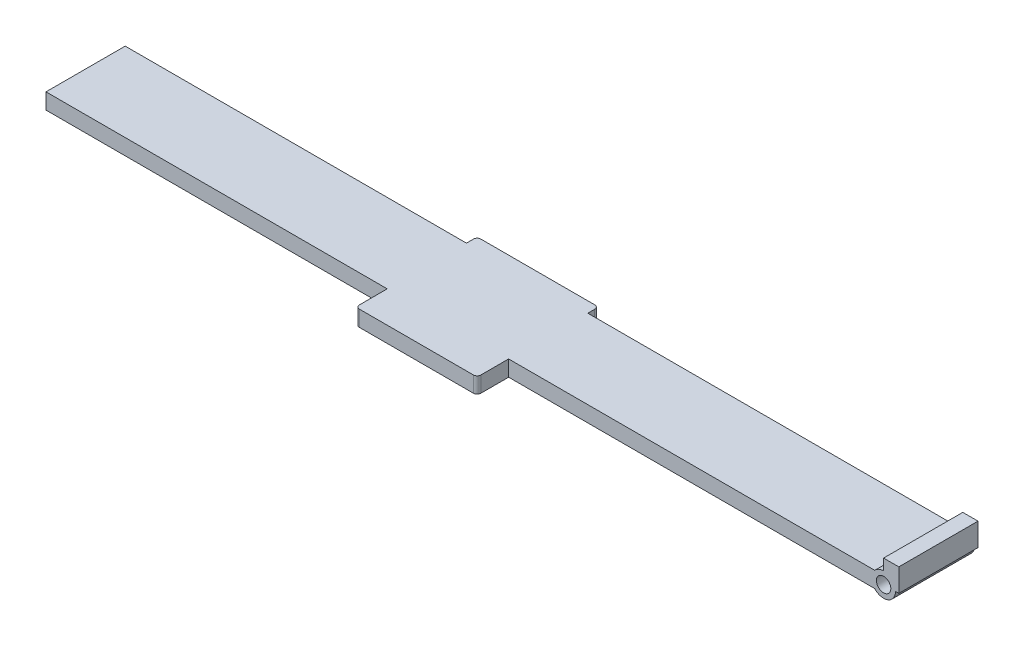
SolidWorks part; units mm, degrees
ref_plane "Front Plane" through (0, 0, 0) normal (0, 0, 1) x (1, 0, 0)
ref_plane "Top Plane" through (0, 0, 0) normal (0, 1, 0) x (1, 0, 0)
ref_plane "Right Plane" through (0, 0, 0) normal (1, 0, 0) x (0, 0, -1)
sketch "Sketch1" plane through (0, 0, 0) normal (0, 1, 0) x (1, 0, 0)
  line L1 (-264.4, -25) -> (264.4, -25)
  line L2 (-264.4, -25) -> (-264.4, 25)
  line L3 (-264.4, 25) -> (264.4, 25)
  line L4 (264.4, -25) -> (264.4, 25)
  line L5 (-264.4, -25) -> (264.4, 25) construction
  line L6 (-264.4, 25) -> (264.4, -25) construction
  point P0 (0, 0)
  dimension "D1" = 528.8
  dimension "D2" = 50
extrude "Extrude2" add sketch "Sketch1" along normal blind 10
sketch "Sketch2" plane through (0, 0, 25) normal (0, 0, 1) x (1, 0, 0)
  line L0 (264.4, 10) -> (264.4, 0) construction
  circle A0 centre (264.4, 5) radius 7.5
  dimension "D1" = 15
extrude "Extrude3" add sketch "Sketch2" against normal blind 50
sketch "Sketch3" plane through (0, 0, 25) normal (0, 0, 1) x (1, 0, 0)
  line L1 (264.4, 5) -> (273.9998, 5)
  line L2 (264.4, 5) -> (264.4, 19.4848)
  line L3 (264.4, 19.4848) -> (273.9998, 19.4848)
  line L4 (273.9998, 5) -> (273.9998, 19.4848)
extrude "Extrude4" add sketch "Sketch3" against normal blind 50
sketch "Sketch5" plane through (0, 0, 25) normal (0, 0, 1) x (1, 0, 0)
  circle A0 centre (264.4, 5) radius 4.5502
extrude "Extrude5" cut sketch "Sketch5" against normal blind 50
sketch "Sketch6" plane through (0, 0, 0) normal (0, 1, 0) x (1, 0, 0)
  line L4 (-48.9687, 29.3464) -> (-48.9687, -42.4541)
  line L5 (-46.548, -44.8747) -> (25.2525, -44.8747)
  line L6 (27.6731, -42.4541) -> (27.6731, 29.3464)
  line L7 (25.2525, 31.7671) -> (-46.548, 31.7671)
  line L8 (-48.9687, 29.3464) -> (-48.9687, -42.4541)
  line L9 (-46.548, -44.8747) -> (25.2525, -44.8747)
  line L10 (27.6731, -42.4541) -> (27.6731, 29.3464)
  line L11 (25.2525, 31.7671) -> (-46.548, 31.7671)
  ellipse E4 centre (-45.7713, -41.6774) end of major axis (-48.2919, -44.1979) minor radius 2.782 (-48.9687, -42.4541) -> (-46.548, -44.8747) ccw
  ellipse E5 centre (24.4758, -41.6774) end of major axis (26.9964, -44.1979) minor radius 2.782 (25.2525, -44.8747) -> (27.6731, -42.4541) ccw
  ellipse E6 centre (24.4758, 28.5697) end of major axis (26.9964, 31.0903) minor radius 2.782 (27.6731, 29.3464) -> (25.2525, 31.7671) ccw
  ellipse E7 centre (-45.7713, 28.5697) end of major axis (-48.2919, 31.0903) minor radius 2.782 (-46.548, 31.7671) -> (-48.9687, 29.3464) ccw
  ellipse E8 centre (-45.7713, -41.6774) end of major axis (-48.2919, -44.1979) minor radius 2.782 (-48.9687, -42.4541) -> (-46.548, -44.8747) ccw
  ellipse E9 centre (24.4758, -41.6774) end of major axis (26.9964, -44.1979) minor radius 2.782 (25.2525, -44.8747) -> (27.6731, -42.4541) ccw
  ellipse E10 centre (24.4758, 28.5697) end of major axis (26.9964, 31.0903) minor radius 2.782 (27.6731, 29.3464) -> (25.2525, 31.7671) ccw
  ellipse E11 centre (-45.7713, 28.5697) end of major axis (-48.2919, 31.0903) minor radius 2.782 (-46.548, 31.7671) -> (-48.9687, 29.3464) ccw
  dimension "D1" = 0
extrude "Extrude6" add sketch "Sketch6" along normal blind 10
